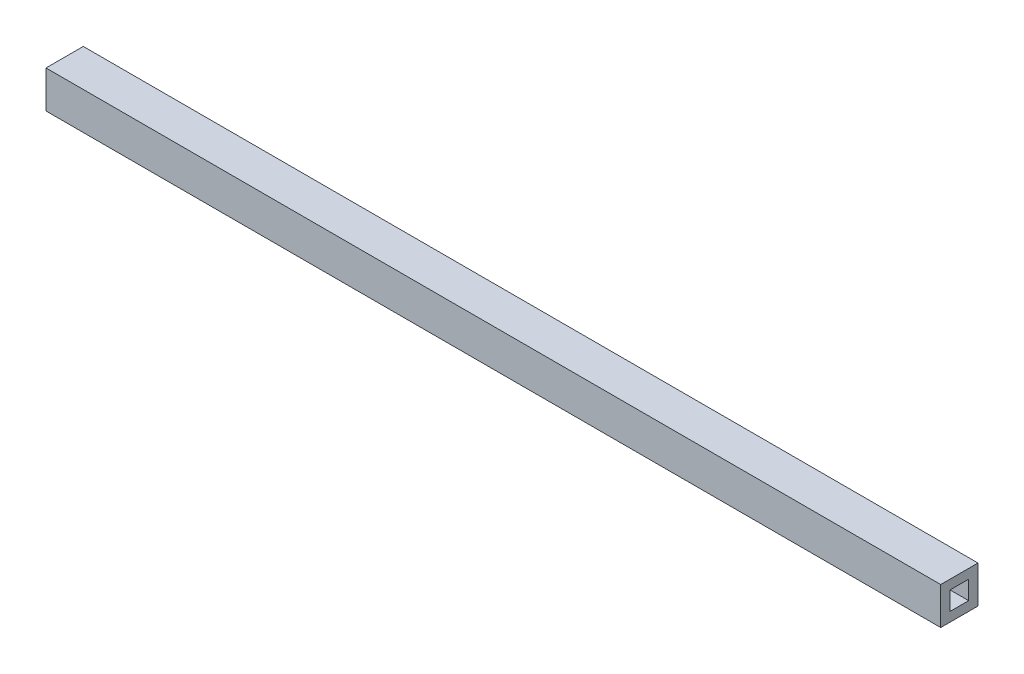
SolidWorks part; units mm, degrees
ref_plane "Front Plane" through (0, 0, 0) normal (0, 0, 1) x (1, 0, 0)
ref_plane "Top Plane" through (0, 0, 0) normal (0, 1, 0) x (1, 0, 0)
ref_plane "Right Plane" through (0, 0, 0) normal (1, 0, 0) x (0, 0, -1)
sketch "Sketch1" plane through (0, 0, 0) normal (0, 0, 1) x (1, 0, 0)
  line L1 (-152.4, -6.35) -> (152.4, -6.35)
  line L2 (-152.4, -6.35) -> (-152.4, 6.35)
  line L3 (-152.4, 6.35) -> (152.4, 6.35)
  line L4 (152.4, -6.35) -> (152.4, 6.35)
  line L5 (-152.4, -6.35) -> (152.4, 6.35) construction
  line L6 (-152.4, 6.35) -> (152.4, -6.35) construction
  point P0 (0, 0)
  dimension "D1" = 304.8
  dimension "D2" = 12.7
extrude "Boss-Extrude1" add sketch "Sketch1" along normal blind 12.7
sketch "Sketch2" plane through (152.4, 0, 0) normal (1, 0, 0) x (0, 0, -1)
  line L1 (-3.175, -3.175) -> (-9.525, -3.175)
  line L2 (-3.175, -3.175) -> (-3.175, 3.175)
  line L3 (-3.175, 3.175) -> (-9.525, 3.175)
  line L4 (-9.525, -3.175) -> (-9.525, 3.175)
  line L5 (-3.175, -3.175) -> (-9.525, 3.175) construction
  line L6 (-3.175, 3.175) -> (-9.525, -3.175) construction
  point P0 (-6.35, 0)
  point P5 (0, 0)
  dimension "D1" = 6.35
  dimension "D2" = 6.35
extrude "Cut-Extrude1" cut sketch "Sketch2" against normal through all
